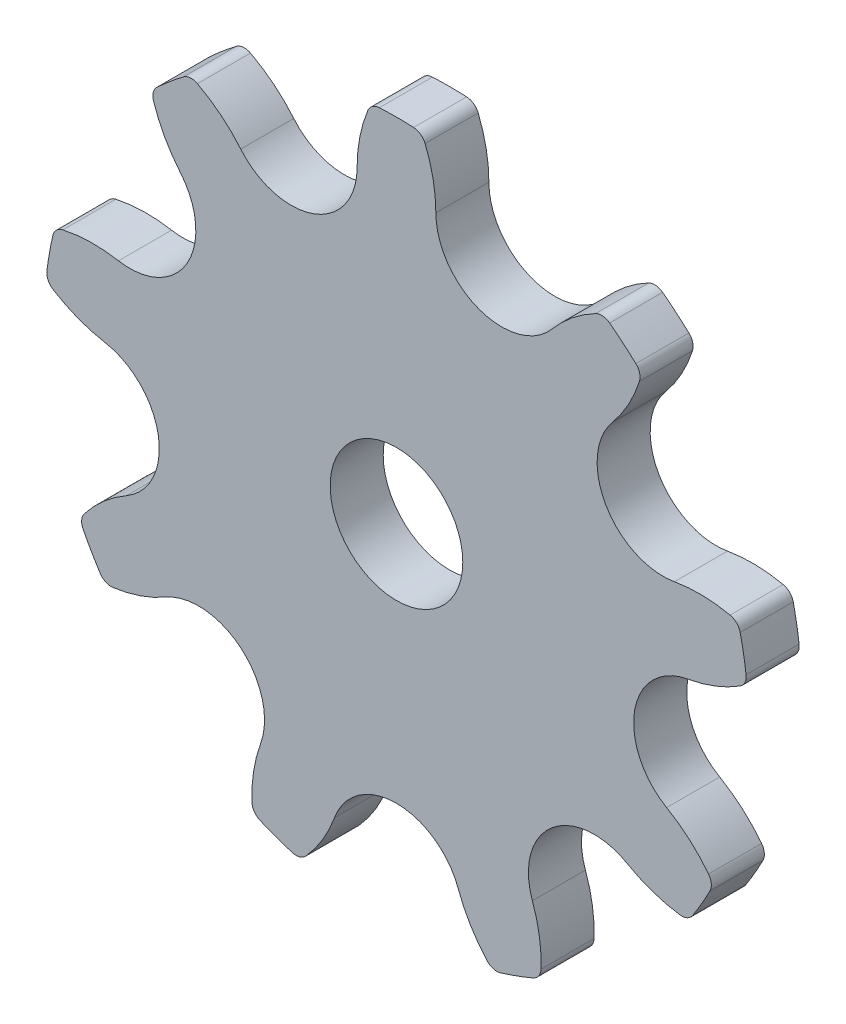
SolidWorks part; units mm, degrees
material "AISI 1020 Steel, Cold Rolled"
ref_plane "Front Plane" through (0, 0, 0) normal (0, 0, 1) x (1, 0, 0)
ref_plane "Top Plane" through (0, 0, 0) normal (0, 1, 0) x (1, 0, 0)
ref_plane "Right Plane" through (0, 0, 0) normal (1, 0, 0) x (0, 0, -1)
sketch "Sketch1" plane through (0, 0, 0) normal (0, 0, 1) x (1, 0, 0)
  arc A0 (2.3749, 17.4465) -> (1.7287, 20.7417) centre (-6.35, 17.4465) ccw
  arc A1 (1.7287, 20.7417) -> (1.0323, 21.2347) centre (0.9937, 20.4419) ccw
  arc A2 (1.0323, 21.2347) -> (-1.0323, 21.2347) centre (0, 0) ccw
  arc A3 (-1.0323, 21.2347) -> (-1.7287, 20.7417) centre (-0.9937, 20.4419) ccw
  arc A4 (-1.7287, 20.7417) -> (-2.3749, 17.4465) centre (6.35, 17.4465) ccw
  arc A5 (-2.3749, 17.4465) -> (-9.3951, 14.8913) centre (-6.35, 17.4465) cw
  arc A6 (-9.3951, 14.8913) -> (-12.0082, 17.0002) centre (-16.0788, 9.2831) ccw
  arc A7 (-12.0082, 17.0002) -> (-12.8586, 16.9303) centre (-12.3786, 16.2982) ccw
  arc A8 (-12.8586, 16.9303) -> (-14.4402, 15.6032) centre (0, 0) ccw
  arc A9 (-14.4402, 15.6032) -> (-14.6568, 14.7779) centre (-13.9011, 15.0206) ccw
  arc A10 (-14.6568, 14.7779) -> (-13.0337, 11.8382) centre (-6.35, 17.4465) ccw
  arc A11 (-13.0337, 11.8382) -> (-16.769, 5.3684) centre (-16.0788, 9.2831) cw
  arc A12 (-16.769, 5.3684) -> (-20.1264, 5.3042) centre (-18.2841, -3.224) ccw
  arc A13 (-20.1264, 5.3042) -> (-20.7329, 4.704) centre (-19.9588, 4.5283) ccw
  arc A14 (-20.7329, 4.704) -> (-21.0914, 2.6708) centre (0, 0) ccw
  arc A15 (-21.0914, 2.6708) -> (-20.7268, 1.8993) centre (-20.3039, 2.5711) ccw
  arc A16 (-20.7268, 1.8993) -> (-17.5938, 0.6907) centre (-16.0788, 9.2831) ccw
  arc A17 (-17.5938, 0.6907) -> (-16.2965, -6.6665) centre (-18.2841, -3.224) cw
  arc A18 (-16.2965, -6.6665) -> (-18.8272, -8.8737) centre (-11.9341, -14.2225) ccw
  arc A19 (-18.8272, -8.8737) -> (-18.906, -9.7234) centre (-18.2001, -9.3603) ccw
  arc A20 (-18.906, -9.7234) -> (-17.8737, -11.5113) centre (0, 0) ccw
  arc A21 (-17.8737, -11.5113) -> (-17.0985, -11.8679) centre (-17.2063, -11.0816) ccw
  arc A22 (-17.0985, -11.8679) -> (-13.9216, -10.78) centre (-18.2841, -3.224) ccw
  arc A23 (-13.9216, -10.78) -> (-8.1987, -15.5821) centre (-11.9341, -14.2225) cw
  arc A24 (-8.1987, -15.5821) -> (-8.7185, -18.8996) centre (0, -18.5662) ccw
  arc A25 (-8.7185, -18.8996) -> (-8.2327, -19.6011) centre (-7.9254, -18.8692) ccw
  arc A26 (-8.2327, -19.6011) -> (-6.2927, -20.3072) centre (0, 0) ccw
  arc A27 (-6.2927, -20.3072) -> (-5.4696, -20.0821) centre (-6.0577, -19.549) ccw
  arc A28 (-5.4696, -20.0821) -> (-3.7354, -17.2066) centre (-11.9341, -14.2225) ccw
  arc A29 (-3.7354, -17.2066) -> (3.7354, -17.2066) centre (0, -18.5662) cw
  arc A30 (3.7354, -17.2066) -> (5.4696, -20.0821) centre (11.9341, -14.2225) ccw
  arc A31 (5.4696, -20.0821) -> (6.2927, -20.3072) centre (6.0577, -19.549) ccw
  arc A32 (6.2927, -20.3072) -> (8.2327, -19.6011) centre (0, 0) ccw
  arc A33 (8.2327, -19.6011) -> (8.7185, -18.8996) centre (7.9254, -18.8692) ccw
  arc A34 (8.7185, -18.8996) -> (8.1987, -15.5821) centre (0, -18.5662) ccw
  arc A35 (8.1987, -15.5821) -> (13.9216, -10.78) centre (11.9341, -14.2225) cw
  arc A36 (13.9216, -10.78) -> (17.0985, -11.8679) centre (18.2841, -3.224) ccw
  arc A37 (17.0985, -11.8679) -> (17.8737, -11.5113) centre (17.2063, -11.0816) ccw
  arc A38 (17.8737, -11.5113) -> (18.906, -9.7234) centre (0, 0) ccw
  arc A39 (18.906, -9.7234) -> (18.8272, -8.8737) centre (18.2001, -9.3603) ccw
  arc A40 (18.8272, -8.8737) -> (16.2965, -6.6665) centre (11.9341, -14.2225) ccw
  arc A41 (16.2965, -6.6665) -> (17.5938, 0.6907) centre (18.2841, -3.224) cw
  arc A42 (17.5938, 0.6907) -> (20.7268, 1.8993) centre (16.0788, 9.2831) ccw
  arc A43 (20.7268, 1.8993) -> (21.0914, 2.6708) centre (20.3039, 2.5711) ccw
  arc A44 (21.0914, 2.6708) -> (20.7329, 4.704) centre (0, 0) ccw
  arc A45 (20.7329, 4.704) -> (20.1264, 5.3042) centre (19.9588, 4.5283) ccw
  arc A46 (20.1264, 5.3042) -> (16.769, 5.3684) centre (18.2841, -3.224) ccw
  arc A47 (16.769, 5.3684) -> (13.0337, 11.8382) centre (16.0788, 9.2831) cw
  arc A48 (13.0337, 11.8382) -> (14.6568, 14.7779) centre (6.35, 17.4465) ccw
  arc A49 (14.6568, 14.7779) -> (14.4402, 15.6032) centre (13.9011, 15.0206) ccw
  arc A50 (14.4402, 15.6032) -> (12.8586, 16.9303) centre (0, 0) ccw
  arc A51 (12.8586, 16.9303) -> (12.0082, 17.0002) centre (12.3786, 16.2982) ccw
  arc A52 (12.0082, 17.0002) -> (9.3951, 14.8913) centre (16.0788, 9.2831) ccw
  arc A53 (9.3951, 14.8913) -> (2.3749, 17.4465) centre (6.35, 17.4465) cw
extrude "Boss-Extrude1" add sketch "Sketch1" against normal blind 3.2
sketch "Sketch2" plane through (0, 0, 0) normal (0, 0, 1) x (1, 0, 0)
  circle A0 centre (0, 0) radius 4
extrude "Cut-Extrude1" cut sketch "Sketch2" against normal blind 10
ref_plane "Plane1" through (0, 0, -1.6) normal (0, 0, 1) x (1, 0, 0)
sketch "Sketch3" plane through (0, 0, -1.6) normal (0, 0, 1) x (1, 0, 0)
  circle A1 centre (0, 0) radius 21.2598 construction
